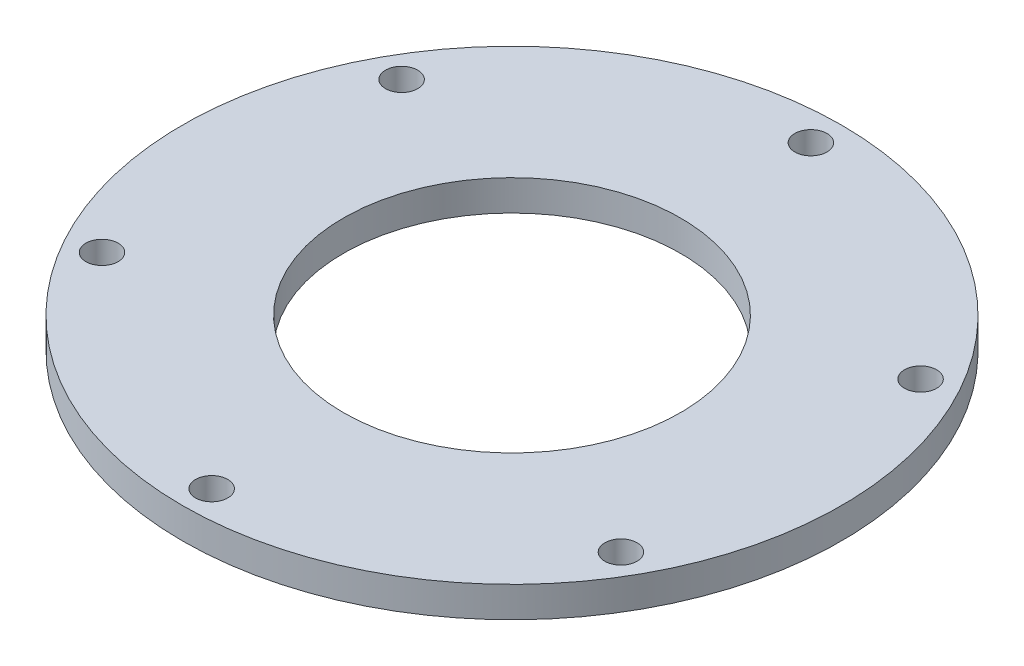
SolidWorks part; units mm, degrees
ref_plane "Alzado" through (0, 0, 0) normal (0, 0, 1) x (1, 0, 0)
ref_plane "Planta" through (0, 0, 0) normal (0, 1, 0) x (1, 0, 0)
ref_plane "Vista lateral" through (0, 0, 0) normal (1, 0, 0) x (0, 0, -1)
sketch "Croquis1" plane through (0, 0, 0) normal (0, 1, 0) x (1, 0, 0)
  circle A0 centre (0, 0) radius 107.5
  dimension "D1" = 215
extrude "Saliente-Extruir1" add sketch "Croquis1" along normal blind 10
sketch "Croquis2" plane through (0, 10, 0) normal (0, 1, 0) x (1, 0, 0)
  circle A0 centre (0, 0) radius 97.5
  dimension "D1" = 195
sketch "Croquis4" plane through (0, 10, 0) normal (0, 1, 0) x (1, 0, 0)
  circle A0 centre (0, 0) radius 55
  dimension "D1" = 110
sketch "Croquis5" plane through (0, 10, 0) normal (0, 1, 0) x (1, 0, 0)
  line L0 (0, 0) -> (0, 129.5423)
hole_wizard "Taladro roscado M12x1.51" positions "Croquis3D1" profile "Croquis6" tap size "M12x1.5" standard "Ansi Metric"
sketch3d "Croquis3D1"
  line L0 (0, 10, 0) -> (0, 10, -129.5423) construction
  circle A0 centre (0, 10, 0) radius 97.5 construction
  point P0 (0, 10, -97.5)
  point P4 (0, 107.5, 0)
sketch "Croquis6" plane through (0, 10, -97.5) normal (1, 0, 0) x (0, 0, 1)
  line L0 (0, 0) -> (0, 34.6545)
  line L1 (0, 34.6545) -> (5.25, 31.5)
  line L2 (5.25, 31.5) -> (5.25, 0)
  line L5 (5.25, 0) -> (0, 0)
  line L10 (0, 34.6545) -> (-5.25, 31.5) construction
  line L11 (0, -6.35) -> (0, 107.95) construction
  dimension "Diámetro de perforador para roscar" = 10.5
  dimension "Profundidad de perforador para roscar" = 31.5
  dimension "Ángulo de perforador" = 118
pattern_circular "MatrizC1" count 6 over 360 about axis through (0, 0, 0.2331) along (0, 1, 0) of "Taladro roscado M12x1.51"
extrude "Cortar-Extruir1" cut sketch "Croquis4" against normal blind 10 contours A0
